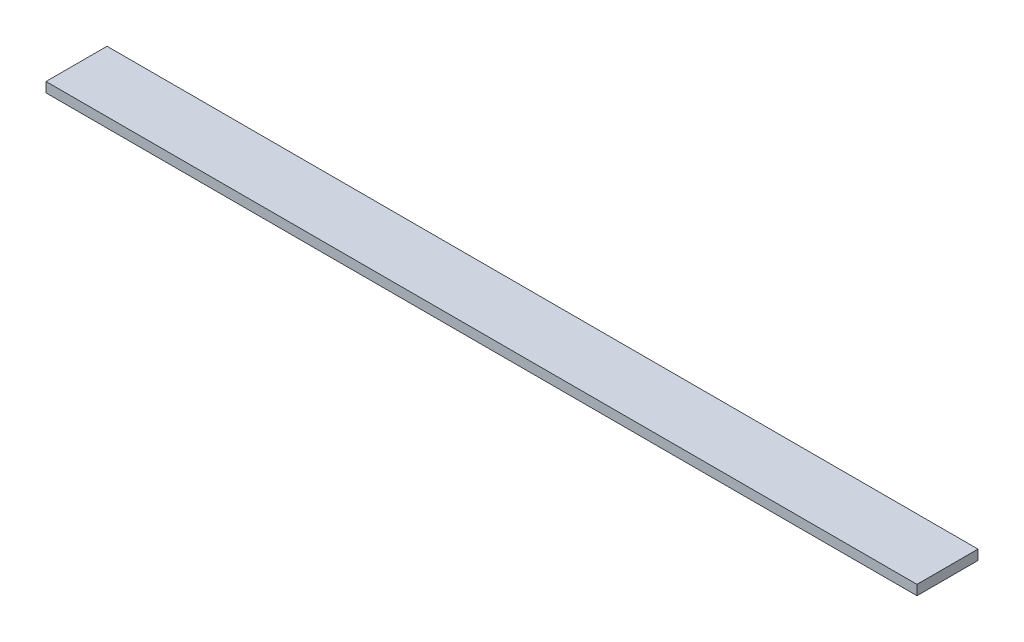
SolidWorks part; units mm, degrees
material "Pine"
ref_plane "Front Plane" through (0, 0, 0) normal (0, 0, 1) x (1, 0, 0)
ref_plane "Top Plane" through (0, 0, 0) normal (0, 1, 0) x (1, 0, 0)
ref_plane "Right Plane" through (0, 0, 0) normal (1, 0, 0) x (0, 0, -1)
sketch "Sketch1" plane through (0, 0, 0) normal (0, 1, 0) x (1, 0, 0)
  line L1 (-1312.2559, 579.5101) -> (2040.5441, 579.5101)
  line L2 (-1312.2559, 579.5101) -> (-1312.2559, 344.5601)
  line L3 (-1312.2559, 344.5601) -> (2040.5441, 344.5601)
  line L4 (2040.5441, 579.5101) -> (2040.5441, 344.5601)
  dimension "D1" = 3352.8
  dimension "D2" = 234.95
extrude "Boss-Extrude1" add sketch "Sketch1" along normal blind 38.1
